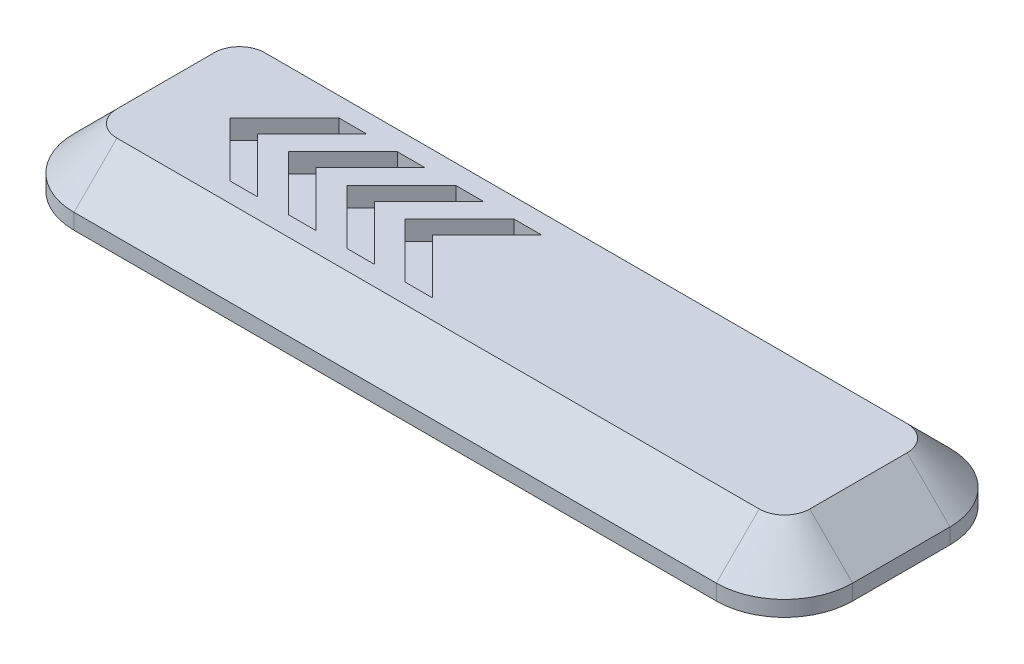
SolidWorks part; units mm, degrees
ref_plane "Front Plane" through (0, 0, 0) normal (0, 0, 1) x (1, 0, 0)
ref_plane "Top Plane" through (0, 0, 0) normal (0, 1, 0) x (1, 0, 0)
ref_plane "Right Plane" through (0, 0, 0) normal (1, 0, 0) x (0, 0, -1)
sketch "Sketch1" plane through (0, 0, 0) normal (0, 1, 0) x (1, 0, 0)
  line L0 (24, -8.5) -> (33, -8.5)
  line L1 (36.5, -5) -> (36.5, 0)
  line L2 (33, 3.5) -> (24, 3.5)
  line L5 (0, -8.5) -> (24, -8.5)
  line L6 (-3.5, 0) -> (-3.5, -5)
  line L7 (24, 3.5) -> (0, 3.5)
  arc A2 (33, -8.5) -> (36.5, -5) centre (33, -5) ccw
  arc A5 (36.5, 0) -> (33, 3.5) centre (33, 0) ccw
  arc A6 (-3.5, -5) -> (0, -8.5) centre (0, -5) ccw
  arc A7 (0, 3.5) -> (-3.5, 0) centre (0, 0) ccw
  dimension "D1" = 12
extrude "Boss-Extrude1" add sketch "Sketch1" along normal blind 3
chamfer "Chamfer1" distance 2.2 angle 45 8 edges at (16.5, 3, 8.5) (35.4749, 3, 7.4749) (-2.4749, 3, 7.4749) (36.5, 3, 2.5) (-3.5, 3, 2.5) (35.4749, 3, -2.4749) (-2.4749, 3, -2.4749) (16.5, 3, -3.5)
sketch "Sketch2" plane through (0, 0, 0) normal (0, -1, 0) x (1, 0, 0)
  line L4 (13.5, 5.5) -> (18.5, 5.5)
  line L5 (12, 4) -> (12, 1)
  line L6 (13.5, -0.5) -> (18.5, -0.5)
  line L7 (20, 4) -> (20, 1)
  line L8 (12, 5.5) -> (20, -0.5) construction
  line L9 (12, -0.5) -> (20, 5.5) construction
  arc A0 (13.5, 5.5) -> (12, 4) centre (13.5, 4) ccw
  arc A1 (12, 1) -> (13.5, -0.5) centre (13.5, 1) ccw
  arc A2 (18.5, -0.5) -> (20, 1) centre (18.5, 1) ccw
  arc A3 (18.5, 5.5) -> (20, 4) centre (18.5, 4) cw
  point P0 (33, 0)
  point P5 (16, 2.5)
  dimension "D1" = 1.5
  dimension "D2" = 8
  dimension "D3" = 6
extrude "Boss-Extrude2" add sketch "Sketch2" along normal blind 3
sketch "Sketch3" plane through (0, 3, 0) normal (0, 1, 0) x (1, 0, 0)
  line L0 (-3.5, -2.5) -> (36.5, -2.5) construction
  line L1 (-3.5, -5) -> (-3.5, 0) construction
  line L2 (36.5, 0) -> (36.5, -5) construction
  line L5 (33, 0.3) -> (0, 0.3)
  line L6 (6.2258, 0.3) -> (4.8116, 0.3)
  line L7 (2.0116, -2.5) -> (4.8116, 0.3)
  line L8 (0, -5.3) -> (33, -5.3)
  line L9 (4.8116, -5.3) -> (6.2258, -5.3)
  line L10 (3.4258, -2.5) -> (6.2258, 0.3)
  line L11 (2.7187, -3.2071) -> (5.5187, -0.4071) construction
  line L12 (3.4258, -2.5) -> (6.2258, -5.3)
  line L13 (2.0116, -2.5) -> (4.8116, -5.3)
  line L14 (9.2258, 0.3) -> (7.8116, 0.3)
  line L15 (5.0116, -2.5) -> (7.8116, 0.3)
  line L16 (7.8116, -5.3) -> (9.2258, -5.3)
  line L17 (6.4258, -2.5) -> (9.2258, 0.3)
  line L18 (6.4258, -2.5) -> (9.2258, -5.3)
  line L19 (5.0116, -2.5) -> (7.8116, -5.3)
  line L20 (-0.5, -2.5) -> (39.5, -2.5) construction
  line L21 (12.2258, 0.3) -> (10.8116, 0.3)
  line L22 (8.0116, -2.5) -> (10.8116, 0.3)
  line L23 (10.8116, -5.3) -> (12.2258, -5.3)
  line L24 (9.4258, -2.5) -> (12.2258, 0.3)
  line L25 (9.4258, -2.5) -> (12.2258, -5.3)
  line L26 (8.0116, -2.5) -> (10.8116, -5.3)
  line L27 (2.5, -2.5) -> (42.5, -2.5) construction
  line L28 (15.2258, 0.3) -> (13.8116, 0.3)
  line L29 (11.0116, -2.5) -> (13.8116, 0.3)
  line L30 (13.8116, -5.3) -> (15.2258, -5.3)
  line L31 (12.4258, -2.5) -> (15.2258, 0.3)
  line L32 (12.4258, -2.5) -> (15.2258, -5.3)
  line L33 (11.0116, -2.5) -> (13.8116, -5.3)
  line L34 (5.5, -2.5) -> (45.5, -2.5) construction
  dimension "D1" = 1
  dimension "D2" = 1
  dimension "D3" = 1
  dimension "D4" = 4
extrude "Cut-Extrude1" cut sketch "Sketch3" against normal blind 1
sketch "Sketch4" plane through (12, 0, 0) normal (-1, 0, 0) x (0, 0, 1)
  line L0 (4, -3) -> (1, -3) construction
  line L1 (2.5, -3) -> (2.5, 0) construction
  line L2 (0, 0) -> (5, 0) construction
  line L3 (1.5, -3) -> (1, -1.5)
  line L8 (3.5, -3) -> (4, -1.5)
  line L10 (1.5, -3) -> (3.5, -3)
  line L11 (1, -1.5) -> (1, 0)
  line L12 (1, 0) -> (4, 0)
  line L13 (4, -1.5) -> (4, 0)
  line L14 (1, -1.5) -> (4, 0) construction
  line L15 (1, 0) -> (4, -1.5) construction
  point P6 (2.5, -0.75)
  point P11 (0, 0)
  point P15 (0, 0)
  point P17 (0, 0)
  dimension "D1" = 2
  dimension "D2" = 3
  dimension "D3" = 1.5
extrude "Cut-Extrude2" cut sketch "Sketch4" against normal blind 5
fillet "Fillet1" radius 1 7 edges at (12.4393, 0, -0.0607) (12.4393, 0, 5.0607) (16, 0, 5.5) (19.5607, 0, 5.0607) (20, 0, 2.5) (19.5607, 0, -0.0607) (16, 0, -0.5)
